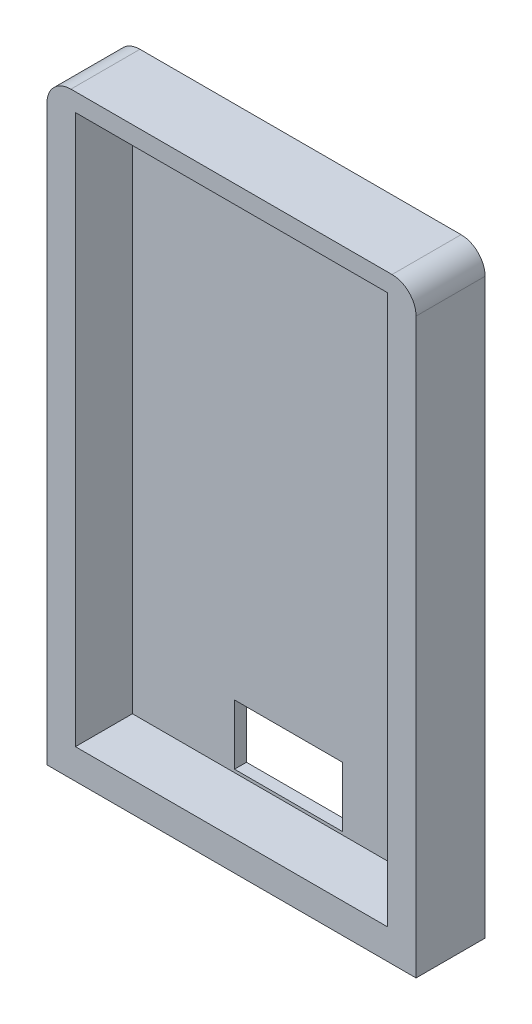
SolidWorks part; units mm, degrees
ref_plane "Plan de face" through (0, 0, 0) normal (0, 0, 1) x (1, 0, 0)
ref_plane "Plan de dessus" through (0, 0, 0) normal (0, 1, 0) x (1, 0, 0)
ref_plane "Plan de droite" through (0, 0, 0) normal (1, 0, 0) x (0, 0, -1)
sketch "Esquisse1" plane through (0, 0, 18.1106) normal (0, 0, 1) x (1, 0, 0)
  line L0 (-10.1492, 9.9032) -> (2.1508, 9.9032)
  line L1 (2.1508, 9.9032) -> (2.1508, -9.9968)
  line L3 (1.2008, -8.9968) -> (1.2008, 9.3032)
  line L4 (1.2008, 9.3032) -> (-9.1992, 9.3032)
  line L5 (-9.1992, 9.3032) -> (-9.1992, -8.9968)
  line L7 (-10.1492, -9.9968) -> (-10.1492, 9.9032)
  line L8 (-9.1992, 9.3032) -> (1.2008, 9.3032) construction
  line L9 (1.2008, 9.3032) -> (1.2008, -7.9968) construction
  line L10 (-9.1992, -7.9968) -> (-9.1992, 9.3032) construction
  line L11 (-9.1992, -8.9968) -> (1.2008, -8.9968)
  line L12 (0.2008, -8.9968) -> (-8.1992, -8.9968) construction
  line L13 (-3.9992, 9.3032) -> (-3.9992, 9.9032) construction
  line L14 (-10.1492, -9.9968) -> (2.1508, -9.9968)
  point P2 (0, 0)
  point P5 (2.1508, -10.064)
  point P19 (0, 0)
  point P20 (0, 0)
  point P22 (0, 0)
  dimension "D1" = 12.3
  dimension "D2" = 0.6
  dimension "D3" = 1
extrude "Boss.-Extru.1" add sketch "Esquisse1" against normal blind 2.3
sketch "Esquisse2" plane through (0, 0, 15.8106) normal (0, 0, -1) x (-1, 0, 0)
  line L0 (-1.2008, 9.3032) -> (9.1992, 9.3032) construction
  line L1 (9.1992, 9.3032) -> (9.1992, -8.9968) construction
  line L2 (9.1992, -8.9968) -> (-1.2008, -8.9968) construction
  line L3 (-1.2008, -8.9968) -> (-1.2008, 9.3032) construction
  line L4 (-1.2008, 9.3032) -> (9.1992, 9.3032)
  line L5 (9.1992, 9.3032) -> (9.1992, -8.9968)
  line L6 (9.1992, -8.9968) -> (-1.2008, -8.9968)
  line L7 (-1.2008, -8.9968) -> (-1.2008, 9.3032)
  line L8 (2.1992, -6.8968) -> (5.7992, -6.8968)
  line L9 (2.3992, -7.0968) -> (5.5992, -7.0968)
  line L10 (2.3992, -7.0968) -> (2.3992, -8.6968)
  line L11 (2.3992, -8.6968) -> (5.5992, -8.6968)
  line L12 (5.5992, -7.0968) -> (5.5992, -8.6968)
  line L13 (5.7992, -6.8968) -> (5.7992, -8.8968)
  line L14 (2.1992, -8.8968) -> (5.7992, -8.8968)
  line L15 (2.1992, -6.8968) -> (2.1992, -8.8968)
  line M13 (-1.2008, -8.9968) -> (-1.2008, 9.3032)
  line M14 (-1.2008, 9.3032) -> (9.1992, 9.3032)
  line M15 (9.1992, 9.3032) -> (9.1992, -8.9968)
  line M16 (9.1992, -8.9968) -> (-1.2008, -8.9968)
  dimension "D1" = 0.2
extrude "Boss.-Extru.2" add sketch "Esquisse2" against normal blind 0.4 contours L15 L8 L13 L14 M13 M16 M15 M14
fillet "Congé1" radius 0.8 2 edges at (-10.1492, 9.9032, 16.9606) (2.1508, 9.9032, 16.9606)
